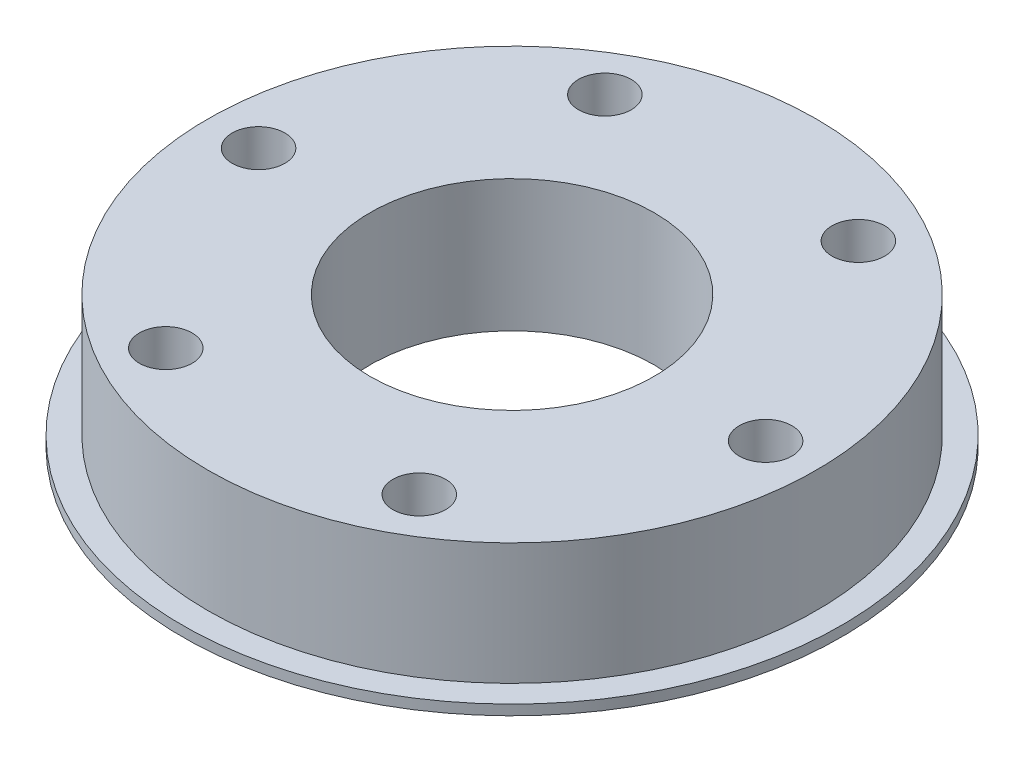
SolidWorks part; units mm, degrees
ref_plane "Front Plane" through (0, 0, 0) normal (0, 0, 1) x (1, 0, 0)
ref_plane "Top Plane" through (0, 0, 0) normal (0, 1, 0) x (1, 0, 0)
ref_plane "Right Plane" through (0, 0, 0) normal (1, 0, 0) x (0, 0, -1)
sketch "Sketch1" plane through (0, 0, 0) normal (0, 1, 0) x (1, 0, 0)
  circle A0 centre (0, 0) radius 30
  point P18 (0, 0)
  dimension "D4" = 60
extrude "Boss-Extrude1" add sketch "Sketch1" along normal blind 13
sketch "Sketch2" plane through (0, 0, 0) normal (0, -1, 0) x (1, 0, 0)
  circle A0 centre (0, 0) radius 32.5
  dimension "D1" = 65
extrude "Boss-Extrude2" add sketch "Sketch2" against normal blind 1
sketch "Sketch3" plane through (0, 0, 0) normal (0, 1, 0) x (1, 0, 0)
  circle A1 centre (0, 0) radius 25 construction
  circle A2 centre (0, 25) radius 1.6
  circle A3 centre (21.6506, 12.5) radius 1.6
  circle A4 centre (21.6506, -12.5) radius 1.6
  circle A5 centre (0, -25) radius 1.6
  circle A6 centre (-21.6506, -12.5) radius 1.6
  circle A7 centre (-21.6506, 12.5) radius 1.6
  point P30 (0, 0)
  dimension "D1" = 50
  dimension "D2" = 3.2
  dimension "D3" = 6
extrude "Cut-Extrude1" cut sketch "Sketch3" along normal blind 3.5
sketch "Sketch4" plane through (0, 0, 0) normal (0, -1, 0) x (1, 0, 0)
  circle A0 centre (0, 0) radius 14
  dimension "D1" = 28
extrude "Cut-Extrude2" cut sketch "Sketch4" against normal blind 51
sketch "Sketch5" plane through (0, 0, 0) normal (0, -1, 0) x (1, 0, 0)
  line L0 (-12.5, 21.6506) -> (0, 0) construction
  line L1 (0, 0) -> (0, 25) construction
  line L2 (0, 25) -> (-21.6506, 12.5) construction
  circle A0 centre (0, 0) radius 25 construction
  circle A1 centre (-12.5, 21.6506) radius 2.6
  circle A2 centre (12.5, 21.6506) radius 2.6
  circle A3 centre (25, 0) radius 2.6
  circle A4 centre (12.5, -21.6506) radius 2.6
  circle A5 centre (-12.5, -21.6506) radius 2.6
  circle A6 centre (-25, 0) radius 2.6
  point P21 (0, 0)
  dimension "D1" = 5.2
  dimension "D2" = 6
extrude "Cut-Extrude3" cut sketch "Sketch5" against normal blind 25
